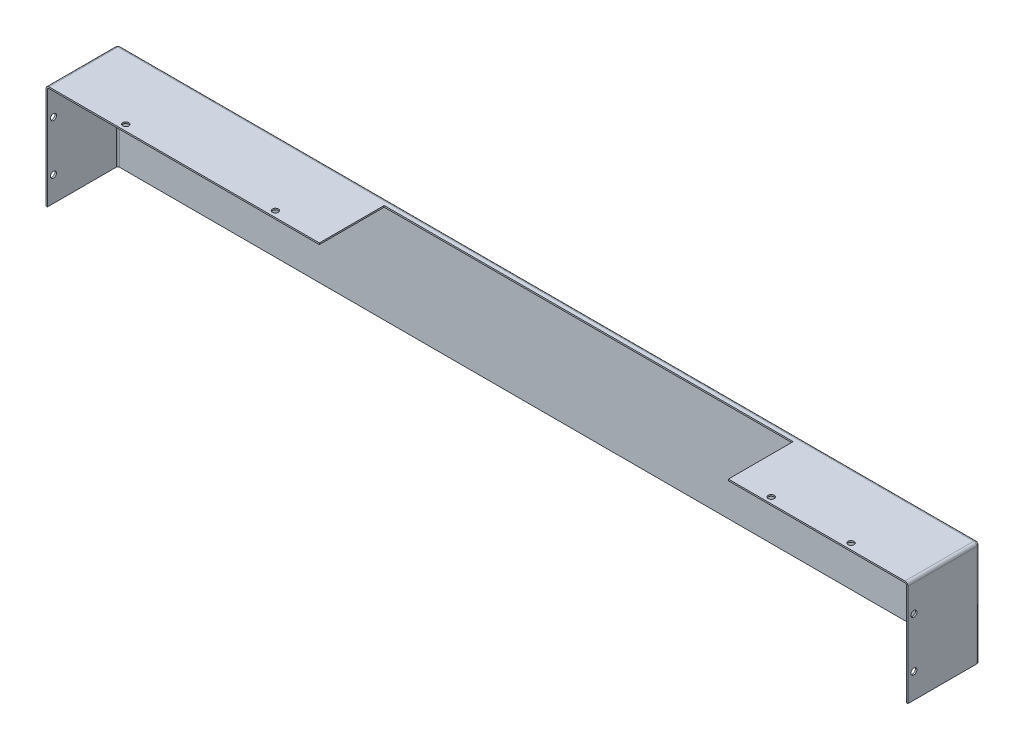
SolidWorks part; units mm, degrees
material "白铁皮表面喷灰白色烤漆"
ref_plane "前基準面" through (0, 0, 0) normal (0, 0, 1) x (1, 0, 0)
ref_plane "上基準面" through (0, 0, 0) normal (0, 1, 0) x (1, 0, 0)
ref_plane "右基準面" through (0, 0, 0) normal (1, 0, 0) x (0, 0, -1)
sketch "草图1" plane through (0, 0, 0) normal (0, 0, 1) x (1, 0, 0)
  line L1 (0, 0) -> (864, 0)
  line L2 (0, 0) -> (0, 105)
  line L3 (0, 105) -> (864, 105)
  line L4 (864, 0) -> (864, 105)
  dimension "D1" = 864
  dimension "D2" = 105
extrude "凸台-拉伸1" add sketch "草图1" along normal blind 72
fillet "圆角1" radius 3 5 edges at (0, 105, 36) (0, 52.5, 0) (432, 105, 0) (864, 52.5, 0) (864, 105, 36)
shell "抽壳1" thickness 1.5
sketch "草图3" plane through (0, 105, 0) normal (0, 1, 0) x (1, 0, 0)
  line L0 (861, -72) -> (3, -72) construction
  line L1 (684, -72) -> (274, -72)
  line L2 (684, -72) -> (684, -7)
  line L3 (684, -7) -> (274, -7)
  line L4 (274, -72) -> (274, -7)
  line L5 (864, -3) -> (864, -72) construction
  dimension "D1" = 180
  dimension "D2" = 65
  dimension "D3" = 410
extrude "切除-拉伸2" cut sketch "草图3" against normal blind 65
sketch "草图4" plane through (864, 0, 0) normal (1, 0, 0) x (0, 0, -1)
  line L0 (-72, 0) -> (-3, 0) construction
  line L1 (-72, 0) -> (-72, 102) construction
  circle A0 centre (-66, 75) radius 3
  circle A1 centre (-66, 25) radius 3
  dimension "D1" = 6
  dimension "D2" = 25
  dimension "D3" = 50
  dimension "D4" = 6
extrude "切除-拉伸3" cut sketch "草图4" against normal through all
sketch "草图5" plane through (0, 105, 0) normal (0, 1, 0) x (1, 0, 0)
  line L0 (861, -72) -> (861, -3) construction
  line L1 (861, -72) -> (684, -72) construction
  line L2 (274, -7) -> (274, -72) construction
  circle A0 centre (721, -66) radius 3
  circle A1 centre (801, -66) radius 3
  circle A2 centre (74, -66) radius 3
  circle A3 centre (224, -66) radius 3
  dimension "D1" = 6
  dimension "D3" = 80
  dimension "D4" = 6
  dimension "D5" = 50
  dimension "D6" = 150
  dimension "D2" = 60
extrude "切除-拉伸4" cut sketch "草图5" against normal blind 10
